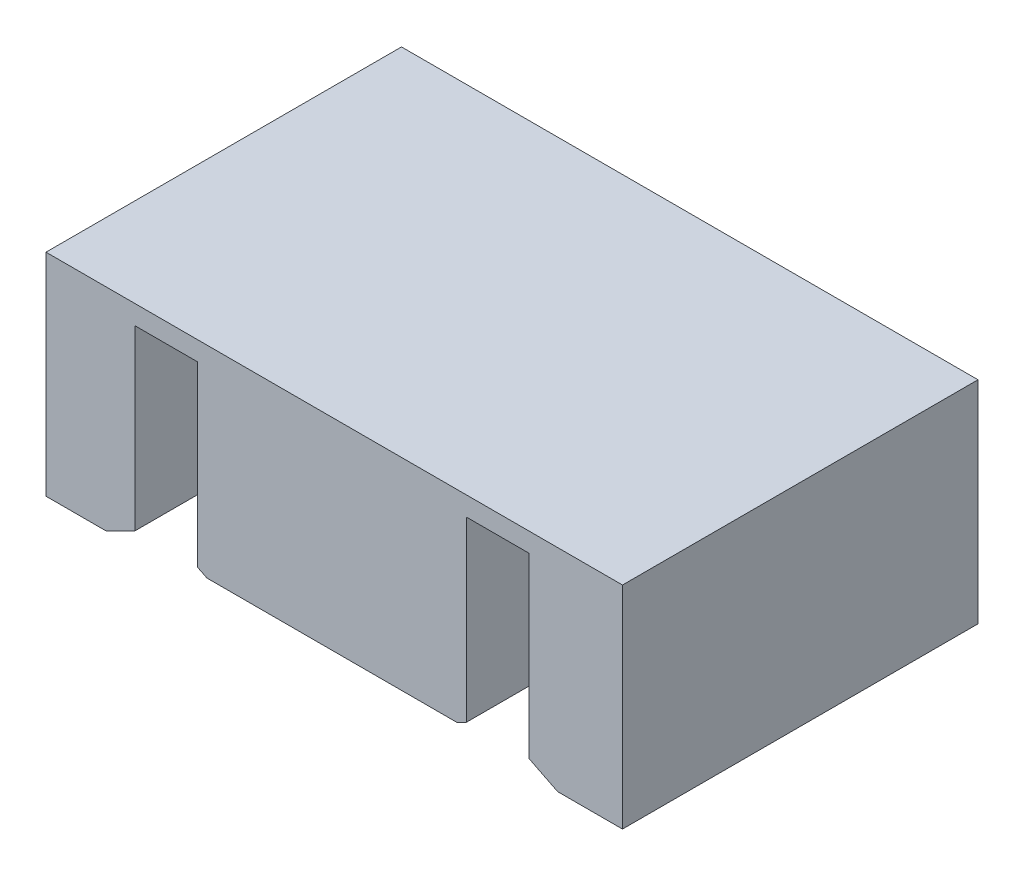
SolidWorks part; units mm, degrees
ref_plane "Front Plane" through (0, 0, 0) normal (0, 0, 1) x (1, 0, 0)
ref_plane "Top Plane" through (0, 0, 0) normal (0, 1, 0) x (1, 0, 0)
ref_plane "Right Plane" through (0, 0, 0) normal (1, 0, 0) x (0, 0, -1)
sketch "Sketch1" plane through (0, 0, 0) normal (0, 1, 0) x (1, 0, 0)
  line L1 (-60, 45) -> (0, 45)
  line L2 (-60, 45) -> (-60, 0)
  line L3 (-60, 0) -> (0, 0)
  line L4 (0, 45) -> (0, 0)
  dimension "D1" = 60
  dimension "D2" = 45
extrude "Boss-Extrude1" add sketch "Sketch1" along normal blind 30
sketch "Sketch2" plane through (0, 0, 0) normal (0, -1, 0) x (-1, 0, 0)
  line L0 (60, 45) -> (60, 0) construction
  line L1 (50.75, 7) -> (44.25, 7)
  line L2 (50.75, 7) -> (50.75, 29)
  line L3 (50.75, 29) -> (44.25, 29)
  line L4 (44.25, 7) -> (44.25, 29)
  line L5 (16.25, 7) -> (9.75, 7)
  line L6 (16.25, 7) -> (16.25, 29)
  line L7 (16.25, 29) -> (9.75, 29)
  line L8 (9.75, 7) -> (9.75, 29)
  line L10 (0, 0) -> (0, 45) construction
  line L12 (0, 45) -> (60, 45) construction
  point P10 (0, 0)
  point P13 (0, 0)
  point P14 (0, 0)
  point P15 (0, 0)
  dimension "D1" = 22
  dimension "D2" = 6.5
  dimension "D3" = 9.25
  dimension "D4" = 6.5
  dimension "D5" = 22
  dimension "D6" = 9.75
  dimension "D7" = 16
extrude "Cut-Extrude1" cut sketch "Sketch2" against normal blind 20
sketch "Sketch4" plane through (0, 0, -45) normal (0, 0, -1) x (-1, 0, 0)
  line L0 (11.5, 0) -> (28.3, 0)
  line L1 (0, 0) -> (60, 0) construction
  arc A0 (28.3, 0) -> (42.6119, 6.1301) centre (38.1836, -3.3031) cw
  arc A1 (42.6119, 6.1301) -> (46.2306, 12.0745) centre (44.0992, 9.2984) ccw
  arc A2 (46.2306, 12.0745) -> (11.5, 0) centre (32.8331, -5.3756) ccw
  dimension "D3" = 3.5
  dimension "D4" = 10.4209
  dimension "D7" = 22
  dimension "D1" = 16.8
  dimension "D2" = 11.5
  dimension "D5" = 3.3031
  dimension "D6" = 9.2984
extrude "Cut-Extrude2" cut sketch "Sketch4" against normal blind 10
chamfer "Chamfer3" distance 3 distance2 1.5 6 edges at (-13, 0, -7) (-9.75, 0, -18) (-16.25, 0, -18) (-44.25, 0, -18) (-47.5, 0, -7) (-50.75, 0, -18)
sketch "Sketch5" plane through (-60, 0, 0) normal (-1, 0, 0) x (0, 0, 1)
  line L0 (0, 30) -> (0, 0) construction
  line L1 (-45, 30) -> (0, 30)
  line L2 (-45, 30) -> (-45, 22)
  line L4 (0, 30) -> (0, 0)
  line L5 (-45, 22) -> (-8, 22)
  line L6 (-8, 22) -> (-8, 0)
  line L7 (-45, 0) -> (0, 0) construction
  line L8 (-8, 0) -> (0, 0)
  dimension "D1" = 8
  dimension "D2" = 8
extrude "Cut-Extrude3" cut sketch "Sketch5" against normal up to next
sketch "Sketch6" plane through (0, 0, 0) normal (0, -1, 0) x (-1, 0, 0)
  line L0 (0, 8) -> (6.75, 8) construction
  line L1 (44.25, 39) -> (16.25, 39)
  line L2 (44.25, 39) -> (44.25, 8)
  line L3 (44.25, 8) -> (16.25, 8)
  line L4 (16.25, 39) -> (16.25, 8)
  line L5 (44.25, 29) -> (44.25, 8) construction
  line L7 (16.25, 8) -> (16.25, 29) construction
  dimension "D1" = 31
extrude "Cut-Extrude4" cut sketch "Sketch6" against normal blind 1
sketch "Sketch7" plane through (0, 0, -29) normal (0, 0, 1) x (1, 0, 0)
  line L0 (-16.25, 20) -> (-16.25, 1.5) construction
  line L1 (-9.75, 20) -> (-16.25, 20)
  line L2 (-9.75, 20) -> (-9.75, 12)
  line L3 (-9.75, 12) -> (-16.25, 12)
  line L4 (-16.25, 20) -> (-16.25, 12)
  line L5 (-50.75, 20) -> (-50.75, 1.5) construction
  line L6 (-44.25, 20) -> (-50.75, 20)
  line L7 (-44.25, 20) -> (-44.25, 12)
  line L8 (-44.25, 12) -> (-50.75, 12)
  line L9 (-50.75, 20) -> (-50.75, 12)
  dimension "D1" = 8
  dimension "D2" = 8
extrude "Cut-Extrude5" cut sketch "Sketch7" against normal blind 6
chamfer "Chamfer4" distance 2 angle 45 2 edges at (-13, 12, -29) (-47.5, 12, -29)
